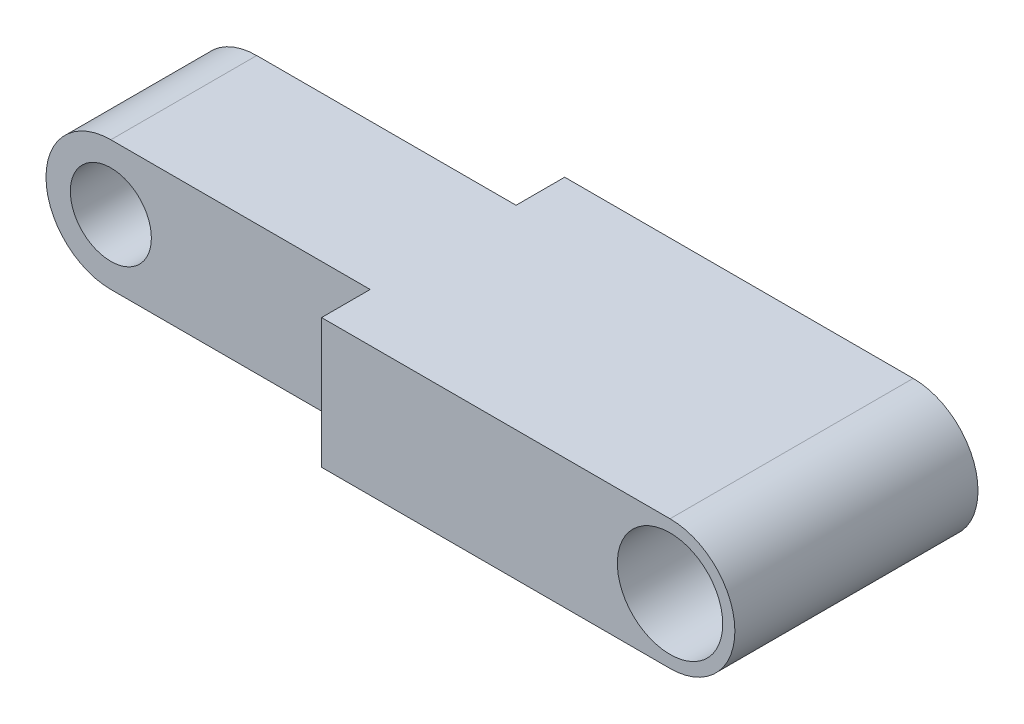
SolidWorks part; units mm, degrees
ref_plane "前视基准面" through (0, 0, 0) normal (0, 0, 1) x (1, 0, 0)
ref_plane "上视基准面" through (0, 0, 0) normal (0, 1, 0) x (1, 0, 0)
ref_plane "右视基准面" through (0, 0, 0) normal (1, 0, 0) x (0, 0, -1)
sketch "草图1" plane through (0, 0, 0) normal (0, 0, 1) x (1, 0, 0)
  line L0 (0, 0) -> (118.3, 0) construction
  line L1 (0, 0) -> (0, 88.2984) construction
  line L2 (-75, 0) -> (75, 0) construction
  line L7 (-75, 16) -> (75, 16)
  line L8 (-75, -16) -> (75, -16)
  arc A0 (-75, 16) -> (-75, -16) centre (-75, 0) ccw
  arc A1 (75, -16) -> (75, 16) centre (75, 0) ccw
  point P6 (0, 0)
  point P11 (0, 0)
  dimension "D2" = 16
  dimension "D1" = 150
extrude "凸台-拉伸1" add sketch "草图1" along normal blind 60
sketch "草图2" plane through (0, 0, 60) normal (0, 0, 1) x (1, 0, 0)
  circle A1 centre (75, 0) radius 13
  dimension "D2" = 26
extrude "切除-拉伸1" cut sketch "草图2" against normal blind 25
sketch "草图3" plane through (0, 0, 35) normal (0, 0, 1) x (1, 0, 0)
  circle A1 centre (75, 0) radius 8.25
  dimension "D2" = 16.5
extrude "切除-拉伸3" cut sketch "草图3" against normal up to next
sketch "草图4" plane through (0, 0, 60) normal (0, 0, 1) x (1, 0, 0)
  circle A0 centre (-75, 0) radius 10
  dimension "D1" = 20
extrude "切除-拉伸4" cut sketch "草图4" against normal up to next
sketch "草图5" plane through (0, 0, 60) normal (0, 0, 1) x (1, 0, 0)
  line L0 (-11, 16) -> (-11, -16)
  line L1 (75, 16) -> (-75, 16) construction
  line L2 (-75, -16) -> (75, -16) construction
  line L3 (-75, -16) -> (-11, -16)
  line L4 (-11, 16) -> (-75, 16)
  circle A0 centre (-75, 0) radius 10 construction
  circle A1 centre (-75, 0) radius 10 construction
  arc A2 (-75, 16) -> (-75, -16) centre (-75, 0) ccw construction
  arc A3 (-75, 16) -> (-75, -16) centre (-75, 0) ccw
  dimension "D1" = 64
extrude "切除-拉伸5" cut sketch "草图5" against normal blind 12
ref_plane "基准面1" through (0, 0, 30) normal (0, 0, 1) x (1, 0, 0)
mirror "镜向1" about plane through (0, 0, 30) normal (0, 0, 1) of "切除-拉伸5"
